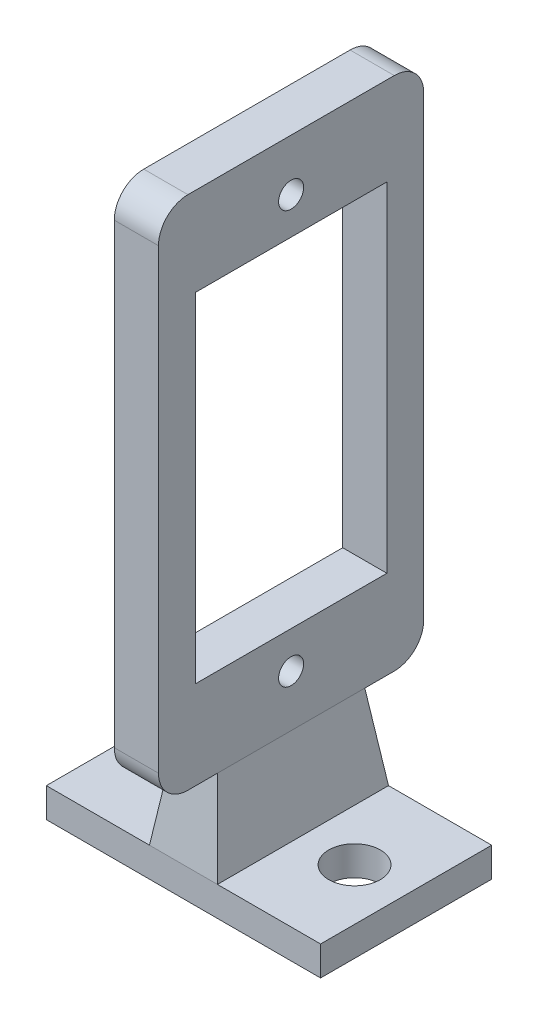
SolidWorks part; units mm, degrees
ref_plane "Plano frontal" through (0, 0, 0) normal (0, 0, 1) x (1, 0, 0)
ref_plane "Plano superior" through (0, 0, 0) normal (0, 1, 0) x (1, 0, 0)
ref_plane "Plano direito" through (0, 0, 0) normal (1, 0, 0) x (0, 0, -1)
sketch "Esboço1" plane through (0, 0, 0) normal (1, 0, 0) x (0, 0, -1)
  line L1 (-9, -17.5) -> (9, -17.5)
  line L2 (-9, -17.5) -> (-9, 17.5)
  line L3 (-9, 17.5) -> (9, 17.5)
  line L4 (9, -17.5) -> (9, 17.5)
  line L5 (-9, -17.5) -> (9, 17.5) construction
  line L6 (-9, 17.5) -> (9, -17.5) construction
  point P0 (0, 0)
  dimension "D1" = 35
  dimension "D2" = 18
extrude "Ressalto-extrusão1" add sketch "Esboço1" along normal mid plane 3
sketch "Esboço2" plane through (1.5, 0, 0) normal (1, 0, 0) x (0, 0, -1)
  line L1 (6.5, -11.5) -> (-6.5, -11.5)
  line L2 (6.5, -11.5) -> (6.5, 11.5)
  line L3 (6.5, 11.5) -> (-6.5, 11.5)
  line L4 (-6.5, -11.5) -> (-6.5, 11.5)
  line L5 (6.5, -11.5) -> (-6.5, 11.5) construction
  line L6 (6.5, 11.5) -> (-6.5, -11.5) construction
  point P0 (0, 0)
  dimension "D1" = 13
  dimension "D2" = 23
extrude "Corte-extrusão1" cut sketch "Esboço2" against normal up to next
sketch "Esboço3" plane through (-1.5, 0, 0) normal (-1, 0, 0) x (0, 0, 1)
  line L0 (-12.3301, 0) -> (12.3301, 0) construction
  circle A0 centre (0, 14) radius 0.85
  circle A1 centre (0, -14) radius 0.85
  dimension "D1" = 1.7
  dimension "D2" = 14
extrude "Corte-extrusão2" cut sketch "Esboço3" against normal up to next
fillet "Filete1" radius 2 4 edges at (0, -17.5, 9) (0, -17.5, -9) (0, 17.5, 9) (0, 17.5, -9)
sketch "Esboço4" plane through (0, -17.5, 0) normal (0, -1, 0) x (1, 0, 0)
  line L0 (-1.5, -7) -> (-1.5, 7) construction
  line L1 (-1.5, -5) -> (1.5, -5)
  line L2 (-1.5, -5) -> (-1.5, 5)
  line L3 (-1.5, 5) -> (1.5, 5)
  line L4 (1.5, -5) -> (1.5, 5)
  line L5 (1.5, -7) -> (1.5, 7) construction
  point P9 (1.5, 0)
  dimension "D1" = 10
extrude "Ressalto-extrusão2" add sketch "Esboço4" along normal blind 5.73 draft 8 draft outward yes
sketch "Esboço5" plane through (0, -23.23, 0) normal (0, -1, 0) x (1, 0, 0)
  line L0 (-2.3053, -5.8053) -> (2.3053, -5.8053) construction
  line L1 (-9.3053, 5.8053) -> (9.3053, 5.8053)
  line L2 (-9.3053, 5.8053) -> (-9.3053, -5.8053)
  line L3 (-9.3053, -5.8053) -> (9.3053, -5.8053)
  line L4 (9.3053, 5.8053) -> (9.3053, -5.8053)
  line L5 (2.3053, 5.8053) -> (-2.3053, 5.8053) construction
  line L8 (2.3053, -5.8053) -> (2.3053, 5.8053) construction
  point P9 (0, -5.8053)
  dimension "D1" = 7
extrude "Ressalto-extrusão3" add sketch "Esboço5" along normal blind 2
sketch "Esboço7" plane through (0, -25.23, 0) normal (0, -1, 0) x (1, 0, 0)
  line L0 (0, 4.0691) -> (0, -3.2907) construction
  line L1 (-9.3053, 5.8053) -> (-9.3053, -5.8053) construction
  circle A0 centre (-5.8053, 0) radius 1.75
  circle A1 centre (5.8053, 0) radius 1.75
  dimension "D1" = 3.5
  dimension "D2" = 3.5
extrude "Corte-extrusão4" cut sketch "Esboço7" against normal up to next
